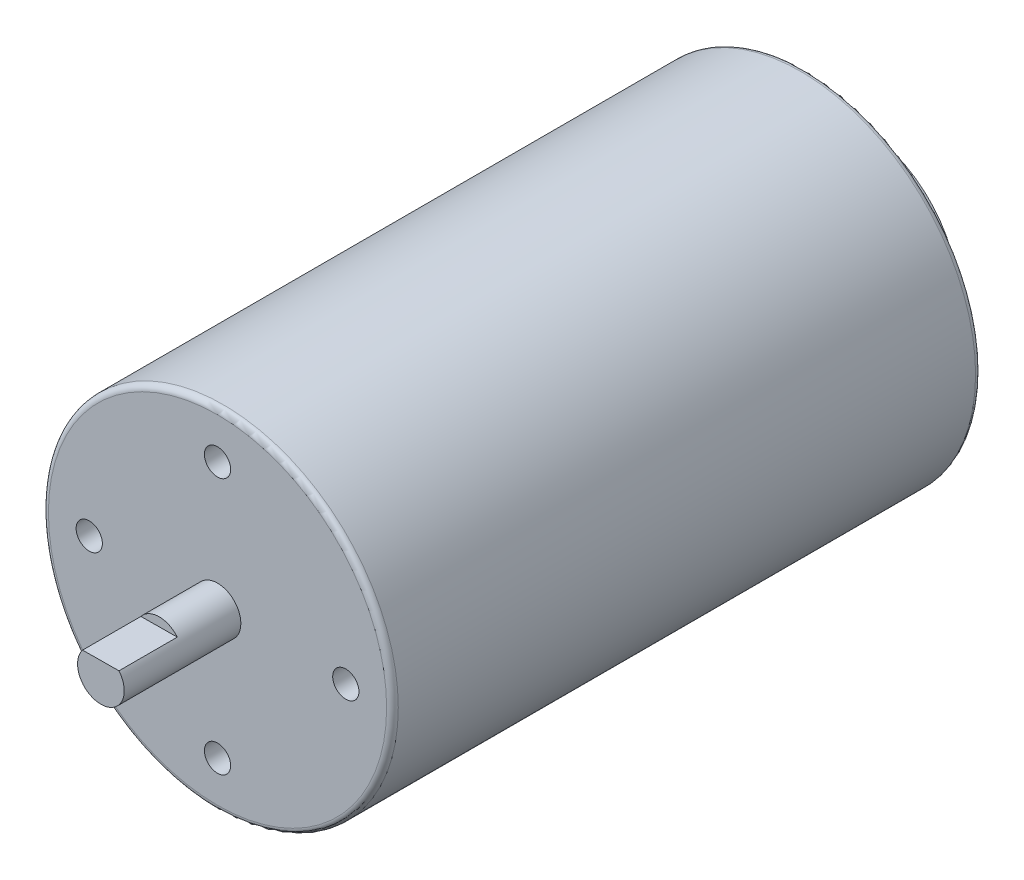
SolidWorks part; units mm, degrees
ref_plane "Plan de face" through (0, 0, 0) normal (1, 0, 0) x (0, 1, 0)
ref_plane "Plan de dessus" through (0, 0, 0) normal (0, 0, 1) x (0, 1, 0)
ref_plane "Plan de droite" through (0, 0, 0) normal (0, 1, 0) x (-1, 0, 0)
sketch "Esquisse1" plane through (0, 0, 0) normal (0, 0, 1) x (0, 1, 0)
  circle A0 centre (0, 0) radius 30
  dimension "D1" = 60
extrude "Boss.-Extru.1" add sketch "Esquisse1" along normal blind 101
sketch "Esquisse2" plane through (0, 0, 101) normal (0, 0, 1) x (1, 0, 0)
  circle A0 centre (0, 0) radius 4
  dimension "D1" = 8
extrude "Boss.-Extru.2" add sketch "Esquisse2" along normal blind 20
sketch "Esquisse3" plane through (0, 0, 121) normal (0, 0, 1) x (1, 0, 0)
  line L0 (-3.1427, 2.4746) -> (3.102, 2.5254)
  arc A0 (-3.1427, 2.4746) -> (3.102, 2.5254) centre (0, 0) cw
  circle A1 centre (0, 0) radius 4 construction
  point P6 (-0.0203, 2.5)
  dimension "D1" = 2.5
extrude "Enlèv. mat.-Extru.1" cut sketch "Esquisse3" against normal blind 10
fillet "Congé1" radius 1 2 edges at (30, 0, 0) (30, 0, 101)
sketch "Esquisse4" plane through (0, 0, 0) normal (0, 0, -1) x (1, 0, 0)
  circle A0 centre (0, 0) radius 17
  dimension "D1" = 34
extrude "Boss.-Extru.3" add sketch "Esquisse4" along normal blind 9
sketch "Esquisse5" plane through (0, 0, 101) normal (0, 0, 1) x (1, 0, 0)
  circle A0 centre (0, 22) radius 2.25
  circle A2 centre (22, 0) radius 2.25
  circle A3 centre (0, -22) radius 2.25
  circle A4 centre (-22, 0) radius 2.25
  dimension "D1" = 4.5
  dimension "D2" = 22
  dimension "D3" = 4
extrude "Enlèv. mat.-Extru.2" cut sketch "Esquisse5" against normal blind 9
sketch "Esquisse7" plane through (0, 0, 0) normal (1, 0, 0) x (0, 1, 0)
  line L0 (-30, 100) -> (30, 100) construction
  line L1 (-20, 90) -> (0, 90)
  line L2 (-20, 90) -> (-20, 11)
  line L3 (-20, 11) -> (0, 11)
  line L4 (0, 90) -> (0, 11)
  line L5 (30, 1) -> (-30, 1) construction
  dimension "D1" = 10
  dimension "D2" = 10
  dimension "D3" = 20
  dimension "D4" = 0
revolve "Enlèvement de matière-Révolution1" cut sketch "Esquisse7" angle 360 about L4
